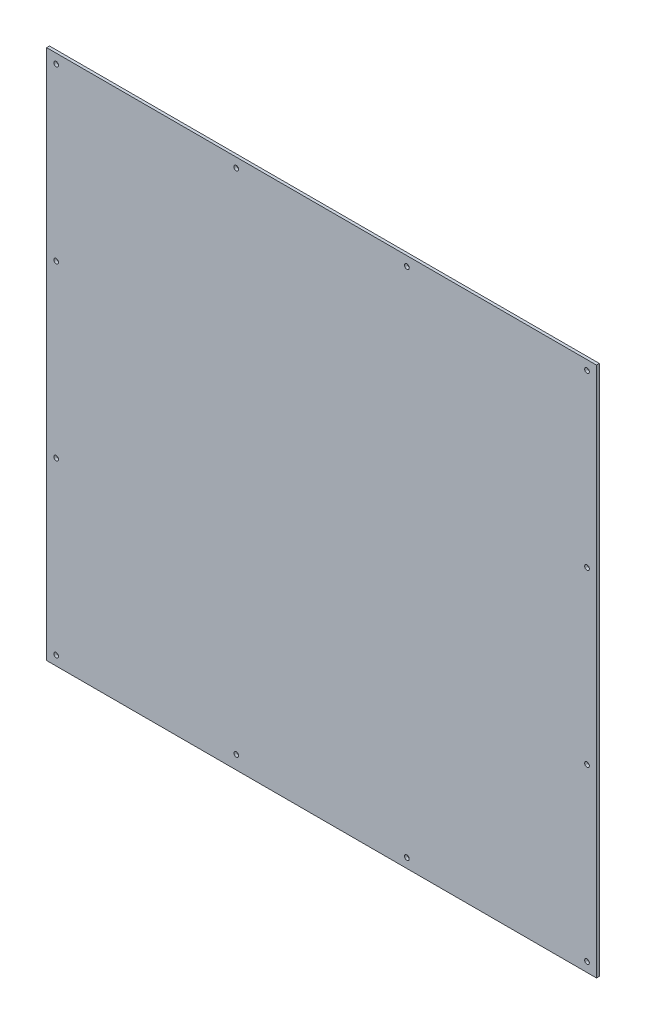
SolidWorks part; units mm, degrees
material "Acrylic (Medium-high impact)"
ref_plane "Front Plane" through (0, 0, 0) normal (0, 0, 1) x (1, 0, 0)
ref_plane "Top Plane" through (0, 0, 0) normal (0, 1, 0) x (1, 0, 0)
ref_plane "Right Plane" through (0, 0, 0) normal (1, 0, 0) x (0, 0, -1)
sketch "Sketch2" plane through (0, 0, 0) normal (0, 0, 1) x (1, 0, 0)
  line L1 (-219.5584, 289.0852) -> (360.4416, 289.0852)
  line L2 (-219.5584, 289.0852) -> (-219.5584, -270.9148)
  line L3 (-219.5584, -270.9148) -> (360.4416, -270.9148)
  line L4 (360.4416, 289.0852) -> (360.4416, -270.9148)
  dimension "D1" = 580
  dimension "D2" = 560
extrude "Boss-Extrude1" add sketch "Sketch2" along normal blind 3
sketch "Sketch3" plane through (0, 0, 3) normal (0, 0, 1) x (1, 0, 0)
  line L0 (360.4416, 289.0852) -> (-219.5584, 289.0852) construction
  line L1 (-219.5584, 289.0852) -> (-219.5584, -270.9148) construction
  line L2 (-219.5584, -270.9148) -> (360.4416, -270.9148) construction
  line L3 (360.4416, -270.9148) -> (360.4416, 289.0852) construction
  circle A0 centre (-209.5584, 279.0852) radius 2.5
  circle A1 centre (-209.5584, 99.0852) radius 2.5
  circle A2 centre (-209.5584, -260.9148) radius 2.5
  circle A3 centre (-209.5584, -80.9148) radius 2.5
  circle A4 centre (350.4416, 279.0852) radius 2.5
  circle A5 centre (350.4416, 99.0852) radius 2.5
  circle A6 centre (350.4416, -80.9148) radius 2.5
  circle A7 centre (350.4416, -260.9148) radius 2.5
  circle A8 centre (-19.5584, -256.6254) radius 2.5
  circle A9 centre (160.4416, -260.9148) radius 2.5
  circle A10 centre (-19.5584, 279.0852) radius 2.5
  circle A11 centre (160.4416, 279.0852) radius 2.5
  dimension "D1" = 5
  dimension "D3" = 10
  dimension "D4" = 10
  dimension "D5" = 10
  dimension "D6" = 180
  dimension "D7" = 180
  dimension "D8" = 10
  dimension "D9" = 10
  dimension "D10" = 5
  dimension "D12" = 10
  dimension "D13" = 5
  dimension "D16" = 5
  dimension "D17" = 180
  dimension "D19" = 5
  dimension "D20" = 180
  dimension "D21" = 10
  dimension "D22" = 5
  dimension "D24" = 5
  dimension "D25" = 190
  dimension "D26" = 10
  dimension "D27" = 5
  dimension "D28" = 10
  dimension "D29" = 190
  dimension "D30" = 5
  dimension "D31" = 180
  dimension "D32" = 10
  dimension "D2" = 10
  dimension "D11" = 10
  dimension "D14" = 180
  dimension "D15" = 10
  dimension "D18" = 10
  dimension "D23" = 190
extrude "Cut-Extrude1" cut sketch "Sketch3" against normal through all
